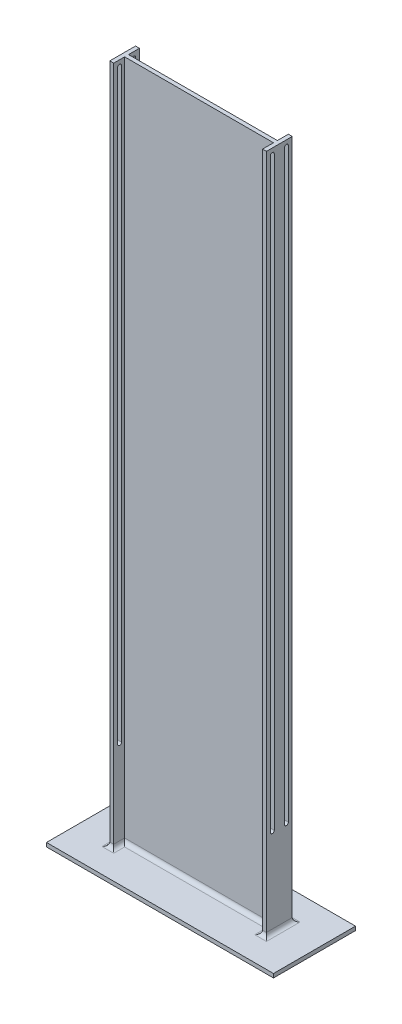
SolidWorks part; units mm, degrees
material "AISI 4340 Steel, annealed"
ref_plane "Front Plane" through (0, 0, 0) normal (0, 0, 1) x (1, 0, 0)
ref_plane "Top Plane" through (0, 0, 0) normal (0, 1, 0) x (1, 0, 0)
ref_plane "Right Plane" through (0, 0, 0) normal (1, 0, 0) x (0, 0, -1)
sketch "Sketch1" plane through (0, 0, 0) normal (1, 0, 0) x (0, 0, -1)
  line L0 (0, 0) -> (-100, 0)
  line L1 (-100, 0) -> (-100, -10)
  line L2 (-100, -10) -> (10, -10)
  line L3 (10, 0) -> (10, 1741.5)
  line L4 (10, 1741.5) -> (0, 1741.5)
  line L5 (0, 1741.5) -> (0, 0)
  line L6 (10, -10) -> (110, -10)
  line L7 (110, -10) -> (110, 0)
  line L8 (110, 0) -> (10, 0)
  dimension "D1" = 1751.5
  dimension "D2" = 10
  dimension "D3" = 10
  dimension "D4" = 100
extrude "Wall extrude" add sketch "Sketch1" along normal mid plane 381
sketch "Sketch2" plane through (190.5, 0, 0) normal (1, 0, 0) x (0, 0, -1)
  line L0 (5, 1741.5) -> (5, -10) construction
  line L1 (10, 1741.5) -> (0, 1741.5) construction
  line L2 (10, 0) -> (10, 1741.5) construction
  line L3 (-100, -10) -> (110, -10) construction
  line L4 (0, 1741.5) -> (38, 1741.5)
  line L6 (0, -10) -> (38, -10)
  line L7 (38, 1741.5) -> (38, -10)
  line L8 (18, 226.5) -> (18, 1726.5)
  line L9 (28, 1726.5) -> (28, 226.5)
  line L10 (-18, 1726.5) -> (-18, 226.5)
  line L11 (-8, 226.5) -> (-8, 1726.5)
  line L12 (0, 1741.5) -> (-28, 1741.5)
  line L13 (-28, 1741.5) -> (-28, -10)
  line L14 (-28, -10) -> (0, -10)
  line L15 (0, 1741.5) -> (0, 0) construction
  arc A0 (28, 1726.5) -> (18, 1726.5) centre (23, 1726.5) ccw
  arc A1 (18, 226.5) -> (28, 226.5) centre (23, 226.5) ccw
  arc A2 (-8, 226.5) -> (-18, 226.5) centre (-13, 226.5) cw
  arc A3 (-18, 1726.5) -> (-8, 1726.5) centre (-13, 1726.5) cw
  dimension "D1" = 10
  dimension "D5" = 10
  dimension "D2" = 13
  dimension "D3" = 15
  dimension "D4" = 15
  dimension "D6" = 13
  dimension "D7" = 236.5
  dimension "D8" = 5
  dimension "D9" = 28
extrude "Right guide extrude" add sketch "Sketch2" along normal blind 10
mirror "Left guide extrude" about plane through (0, 0, 0) normal (1, 0, 0) of "Right guide extrude"
sketch "Sketch3" plane through (0, -10, 0) normal (0, -1, 0) x (1, 0, 0)
  line L11 (190.5, 100) -> (-190.5, 100) construction
  line L12 (-290.5, 100) -> (290.5, 100)
  line L15 (-290.5, 100) -> (-290.5, -110)
  line L16 (-290.5, -110) -> (290.5, -110)
  line L17 (290.5, 100) -> (290.5, -110)
  line L18 (190.5, -110) -> (-190.5, -110) construction
  line L19 (-190.5, 100) -> (-190.5, 28) construction
  line L20 (190.5, 100) -> (190.5, 28) construction
  dimension "D2" = 100
  dimension "D1" = 100
extrude "Bottom foot completion" add sketch "Sketch3" against normal blind 10
sketch "Sketch4" plane through (0, 0, -10) normal (0, 0, -1) x (-1, 0, 0)
  line L0 (-190.5, 0) -> (-190.5, 1741.5) construction
  line L1 (-190.5, 136.5) -> (190.5, 136.5)
  line L2 (-190.5, 136.5) -> (-190.5, 126.5)
  line L3 (-190.5, 126.5) -> (190.5, 126.5)
  line L4 (190.5, 136.5) -> (190.5, 126.5)
  line L5 (190.5, 0) -> (190.5, 1741.5) construction
  line L6 (-190.5, -10) -> (190.5, -10) construction
  dimension "D1" = 146.5
  dimension "D2" = 10
extrude "Platform stopper" add sketch "Sketch4" along normal up to surface (28 mm away) up to face at (195.5, 870.75, -38)
fillet "Structural fillets" radius 10 15 edges at (-200.5, 0, -5) (200.5, 0, -5) (0, 0, 0) (-190.5, 126.5, -24) (190.5, 126.5, -24) (0, 126.5, -10) (190.5, 0, 14) (-190.5, 0, 14) (-195.5, 0, 28) (195.5, 0, 28) (-195.5, 0, -38) (-190.5, 0, -24) (190.5, 0, -24) (195.5, 0, -38) (0, 0, -10)
